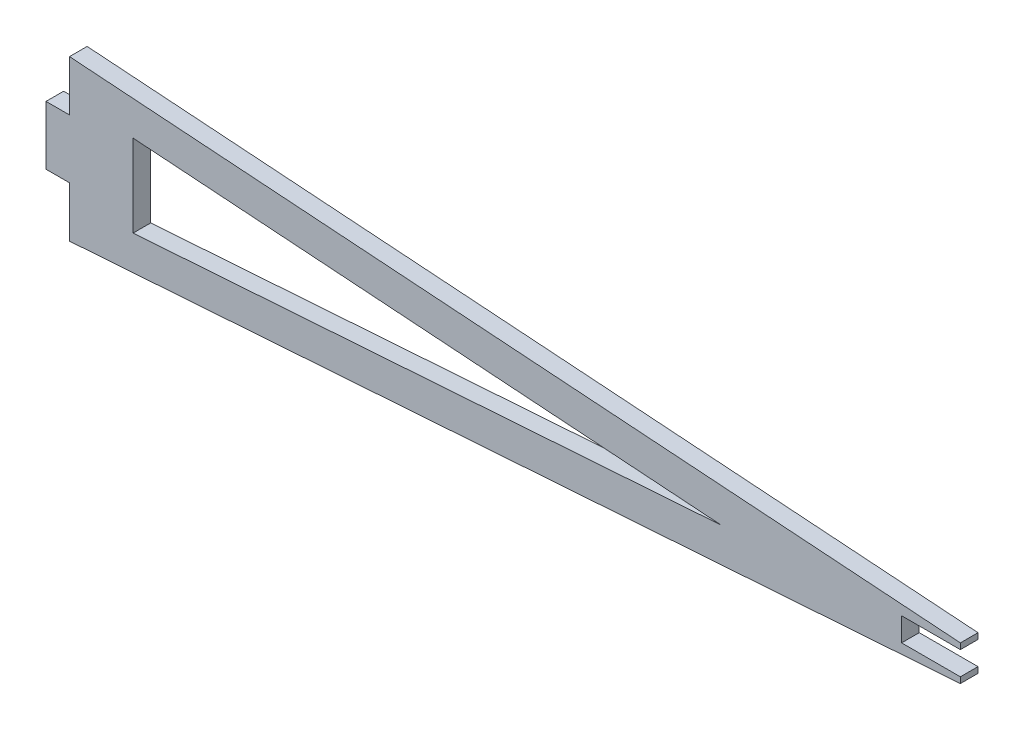
SolidWorks part; units mm, degrees
ref_plane "前视基准面" through (0, 0, 0) normal (0, 0, 1) x (1, 0, 0)
ref_plane "上视基准面" through (0, 0, 0) normal (0, 1, 0) x (1, 0, 0)
ref_plane "右视基准面" through (0, 0, 0) normal (1, 0, 0) x (0, 0, -1)
sketch "Model" plane through (0, 0, 0) normal (0, 0, 1) x (1, 0, 0)
  line L0 (184.4119, 120.0105) -> (204.4188, 120.0105)
  line L1 (204.4119, 170.0105) -> (184.4119, 170.0105)
  line L2 (184.4119, 170.0105) -> (184.4119, 120.0105)
  line L3 (204.4188, 77.0105) -> (204.4188, 120.0105)
  line L4 (204.4119, 170.0105) -> (204.4188, 213.0105)
  line L5 (204.4188, 213.0105) -> (962.3541, 160.0105)
  line L6 (204.4188, 77.0105) -> (962.3541, 130.0105)
  line L7 (962.3541, 130.0105) -> (962.3541, 135.0105)
  line L8 (962.3541, 155.0105) -> (962.3541, 160.0105)
  line L9 (258.5061, 110.0105) -> (258.5061, 180.0105)
  line L10 (258.5061, 110.0105) -> (759.0294, 145.0105)
  line L11 (258.5061, 180.0105) -> (759.0294, 145.0105)
  line L12 (962.3541, 155.0105) -> (912.3541, 155.0105)
  line L13 (962.3541, 135.0105) -> (912.3541, 135.0105)
  line L14 (912.3541, 155.0105) -> (912.3541, 135.0105)
extrude "凸台-拉伸1" add sketch "Model" along normal blind 15
